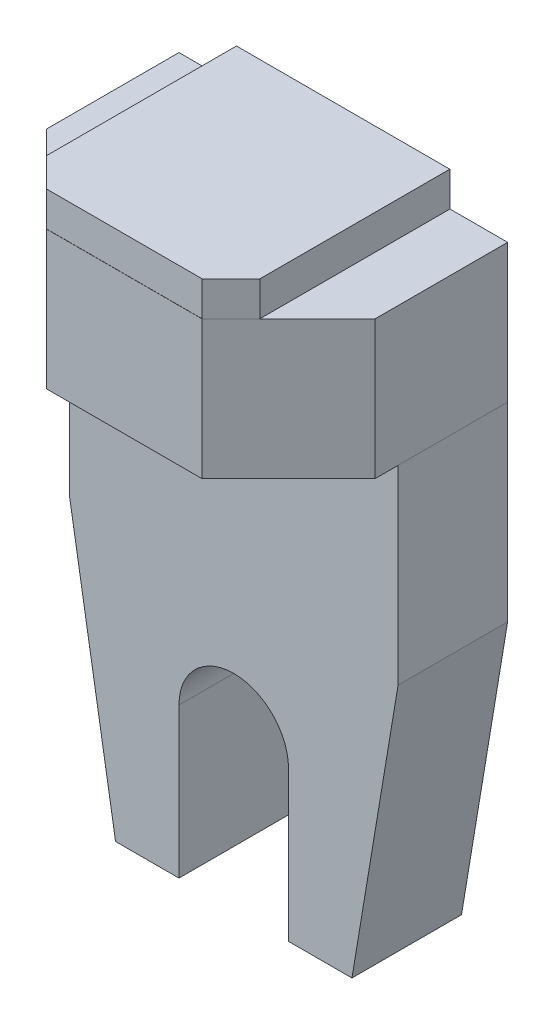
SolidWorks part; units mm, degrees
ref_plane "Front Plane" through (0, 0, 0) normal (0, 0, 1) x (1, 0, 0)
ref_plane "Top Plane" through (0, 0, 0) normal (0, 1, 0) x (1, 0, 0)
ref_plane "Right Plane" through (0, 0, 0) normal (1, 0, 0) x (0, 0, -1)
sketch "Sketch2" plane through (0, 0, 0) normal (0, 0, 1) x (1, 0, 0)
  line L1 (-28.5, -52.5) -> (28.5, -52.5)
  line L2 (-28.5, -52.5) -> (-28.5, 52.5)
  line L3 (-28.5, 52.5) -> (28.5, 52.5)
  line L4 (28.5, -52.5) -> (28.5, 52.5)
  line L5 (-28.5, -52.5) -> (28.5, 52.5) construction
  line L6 (-28.5, 52.5) -> (28.5, -52.5) construction
  point P0 (0, 0)
  dimension "D1" = 105
  dimension "D2" = 57
extrude "Boss-Extrude1" add sketch "Sketch2" along normal blind 19
sketch "Sketch5" plane through (0, 0, 19) normal (0, 0, 1) x (1, 0, 0)
  line L0 (28.5, -52.5) -> (20.5, -52.5)
  line L1 (-28.5, -52.5) -> (28.5, -52.5) construction
  line L2 (20.5, -52.5) -> (28.5, -4.5)
  line L3 (28.5, -52.5) -> (28.5, 52.5) construction
  line L4 (28.5, -4.5) -> (28.5, -52.5)
  dimension "D1" = 8
  dimension "D2" = 48
extrude "Cut-Extrude1" cut sketch "Sketch5" against normal blind 19
sketch "Sketch6" plane through (0, 0, 19) normal (0, 0, 1) x (1, 0, 0)
  line L0 (-28.5, -52.5) -> (-28.5, -4.5)
  line L1 (-28.5, 52.5) -> (-28.5, -52.5) construction
  line L2 (-28.5, -4.5) -> (-20.5, -52.5)
  line L3 (-28.5, -52.5) -> (20.5, -52.5) construction
  line L4 (-20.5, -52.5) -> (-28.5, -52.5)
  dimension "D1" = 8
  dimension "D2" = 48
extrude "Cut-Extrude2" cut sketch "Sketch6" against normal blind 19
sketch "Sketch7" plane through (0, 0, 19) normal (0, 0, 1) x (1, 0, 0)
  line L0 (-9.5, -52.5) -> (-9.5, -26.5)
  line L1 (-20.5, -52.5) -> (20.5, -52.5) construction
  line L2 (-9.5, -52.5) -> (9.5, -52.5)
  line L3 (9.5, -52.5) -> (9.5, -26.5)
  arc A0 (-9.5, -26.5) -> (9.5, -26.5) centre (0, -26.5) cw
  dimension "D1" = 19
  dimension "D2" = 11
  dimension "D3" = 26
extrude "Cut-Extrude3" cut sketch "Sketch7" against normal through all
sketch "Sketch9" plane through (0, 52.5, 0) normal (0, 1, 0) x (1, 0, 0)
  line L0 (-28.5, -23) -> (-13.5, -38)
  line L1 (-28.5, 0) -> (28.5017, 0)
  line L2 (-28.5, 0) -> (-28.5, -23)
  line L3 (-13.5, -38) -> (13.5017, -38)
  line L4 (28.5017, 0) -> (28.5017, -23)
  line L5 (-28.5, 0) -> (28.5017, -38) construction
  line L6 (-28.5, -38) -> (28.5017, 0) construction
  line L7 (13.5017, -38) -> (28.5017, -23)
  point P4 (0.0008, -19)
  point P8 (0, 0)
  dimension "D1" = 38
extrude "Boss-Extrude2" add sketch "Sketch9" against normal blind 24
sketch "Sketch10" plane through (0, 52.5, 0) normal (0, 1, 0) x (1, 0, 0)
  line L0 (-28.5, -23) -> (-28.5, 0) construction
  line L1 (18.5, -0.0299) -> (-18.5, -0.0299)
  line L2 (18.5, -0.0299) -> (18.5, -32.9732)
  line L3 (13.5, -37.9732) -> (-13.5, -37.9732)
  line L4 (-18.5, -0.0299) -> (-18.5, -32.9732)
  line L5 (18.5, -0.0299) -> (-18.5, -37.9732) construction
  line L6 (18.5, -37.9732) -> (-18.5, -0.0299) construction
  line L8 (-13.5, -37.9732) -> (-18.5, -32.9732)
  line L9 (18.5, -32.9732) -> (13.5, -37.9732)
  point P4 (0, -19.0015)
  dimension "D1" = 37
  dimension "D2" = 10
extrude "Boss-Extrude3" add sketch "Sketch10" along normal blind 6
